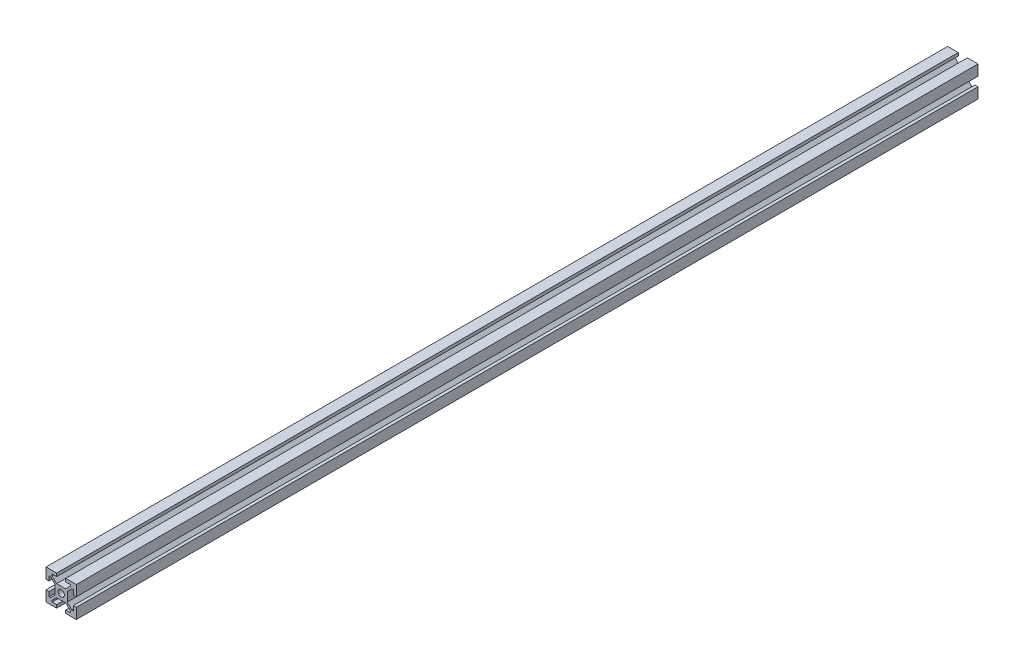
SolidWorks part; units mm, degrees
ref_plane "正面" through (0, 0, 0) normal (0, 0, 1) x (1, 0, 0)
ref_plane "平面" through (0, 0, 0) normal (0, 1, 0) x (1, 0, 0)
ref_plane "右側面" through (0, 0, 0) normal (1, 0, 0) x (0, 0, -1)
sketch "ｽｹｯﾁ2" plane through (0, 0, 0) normal (0, 0, 1) x (1, 0, 0)
  line L0 (0, 0) -> (0, 10) construction
  line L1 (-10, -10) -> (10, -10) construction
  line L2 (-10, -10) -> (-10, 10) construction
  line L3 (-10, 10) -> (10, 10) construction
  line L4 (10, -10) -> (10, 10) construction
  line L5 (-10, -10) -> (10, 10) construction
  line L6 (-10, 10) -> (10, -10) construction
  line L8 (3, 4) -> (-3, 4)
  line L9 (-6, 7) -> (6, 7) construction
  line L10 (-6, 8) -> (-6, 7)
  line L11 (6, 8) -> (6, 7)
  line L12 (-6, 7) -> (-3, 4)
  line L13 (3, 4) -> (6, 7)
  line L14 (-6, 8) -> (-3, 8)
  line L15 (-3, 8) -> (-3, 10)
  line L16 (-3, 10) -> (-10, 10)
  line L17 (6, 8) -> (3, 8)
  line L18 (3, 8) -> (3, 10)
  line L19 (3, 10) -> (10, 10)
  line L20 (7, 6) -> (4, 3)
  line L21 (4, -3) -> (4, 3)
  line L22 (4, -3) -> (7, -6)
  line L23 (8, -6) -> (8, -3)
  line L24 (8, -6) -> (7, -6)
  line L25 (8, -3) -> (10, -3)
  line L26 (10, -3) -> (10, -10)
  line L27 (8, 3) -> (10, 3)
  line L28 (10, 3) -> (10, 10)
  line L29 (8, 6) -> (8, 3)
  line L30 (8, 6) -> (7, 6)
  line L31 (6, -7) -> (3, -4)
  line L32 (-3, -4) -> (3, -4)
  line L33 (-3, -4) -> (-6, -7)
  line L34 (-6, -8) -> (-3, -8)
  line L35 (-6, -8) -> (-6, -7)
  line L36 (-3, -8) -> (-3, -10)
  line L37 (-3, -10) -> (-10, -10)
  line L38 (3, -8) -> (3, -10)
  line L39 (3, -10) -> (10, -10)
  line L40 (6, -8) -> (3, -8)
  line L41 (6, -8) -> (6, -7)
  line L42 (-7, -6) -> (-4, -3)
  line L43 (-4, 3) -> (-4, -3)
  line L44 (-4, 3) -> (-7, 6)
  line L45 (-8, 6) -> (-8, 3)
  line L46 (-8, 6) -> (-7, 6)
  line L47 (-8, 3) -> (-10, 3)
  line L48 (-10, 3) -> (-10, 10)
  line L49 (-8, -3) -> (-10, -3)
  line L50 (-10, -3) -> (-10, -10)
  line L51 (-8, -6) -> (-8, -3)
  line L52 (-8, -6) -> (-7, -6)
  circle A0 centre (0, 0) radius 2.1
  point P0 (0, 0)
  point P11 (0, 10)
  point P14 (0, 4)
  point P17 (0, 7)
  dimension "D8" = 4.2
  dimension "D1" = 20
  dimension "D2" = 6
  dimension "D3" = 2
  dimension "D4" = 4
  dimension "D5" = 12
  dimension "D6" = 6
  dimension "D7" = 4
extrude "ﾎﾞｽ - 押し出し1" add sketch "ｽｹｯﾁ2" along normal blind 594
